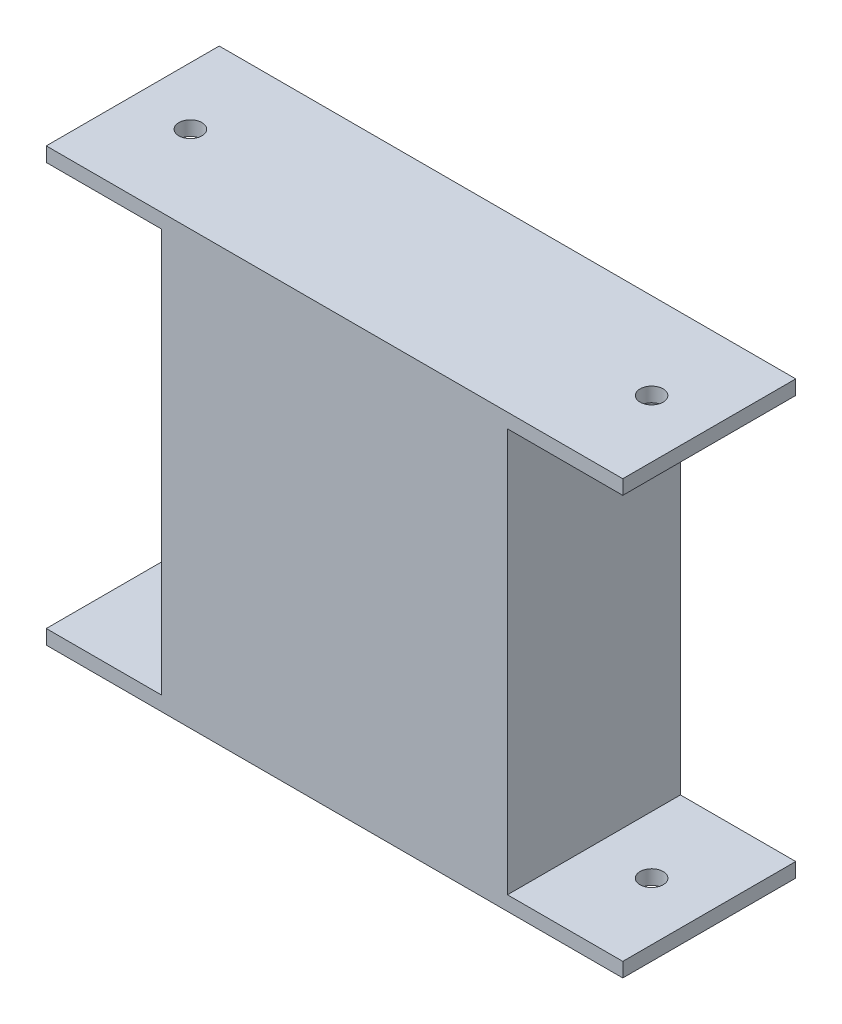
SolidWorks part; units mm, degrees
ref_plane "前视基准面" through (0, 0, 0) normal (0, 0, 1) x (1, 0, 0)
ref_plane "上视基准面" through (0, 0, 0) normal (0, 1, 0) x (1, 0, 0)
ref_plane "右视基准面" through (0, 0, 0) normal (1, 0, 0) x (0, 0, -1)
other "Configuration Table"
sketch "草图1" plane through (0, 0, 0) normal (0, 0, 1) x (1, 0, 0)
  line L0 (-100, 75) -> (100, 75)
  line L1 (-100, -75) -> (100, -75) construction
  line L2 (-100, -75) -> (-100, 75) construction
  line L3 (-100, 75) -> (100, 75) construction
  line L4 (100, -75) -> (100, 75) construction
  line L5 (-100, -75) -> (100, 75) construction
  line L6 (-100, 75) -> (100, -75) construction
  line L7 (-60, -75) -> (60, -75) construction
  line L8 (-60, -75) -> (-60, 75) construction
  line L9 (-60, 75) -> (60, 75) construction
  line L10 (60, -75) -> (60, 75) construction
  line L11 (-60, -75) -> (60, 75) construction
  line L12 (-60, 75) -> (60, -75) construction
  line L13 (-100, -70) -> (100, -70) construction
  line L14 (-100, -70) -> (-100, 70) construction
  line L15 (-100, 70) -> (100, 70) construction
  line L16 (100, -70) -> (100, 70) construction
  line L17 (-100, -70) -> (100, 70) construction
  line L18 (-100, 70) -> (100, -70) construction
  line L19 (100, 75) -> (100, 70)
  line L20 (100, 70) -> (60, 70)
  line L21 (60, 70) -> (60, -70)
  line L22 (60, -70) -> (100, -70)
  line L23 (100, -70) -> (100, -75)
  line L24 (100, -75) -> (-100, -75)
  line L25 (-100, -75) -> (-100, -70)
  line L26 (-100, -70) -> (-60, -70)
  line L27 (-60, -70) -> (-60, 70)
  line L28 (-60, 70) -> (-100, 70)
  line L29 (-100, 70) -> (-100, 75)
  point P0 (0, 0)
  point P6 (0, 0)
  point P11 (0, 0)
  dimension "D1" = 150
  dimension "D2" = 200
  dimension "D3" = 120
  dimension "D4" = 140
extrude "凸台-拉伸1" add sketch "草图1" along normal blind 60
sketch3d "3D草图2"
  point P0 (-14.2591, 19.067, 60)
ref_plane "基准面2" through (0, 0, 60) normal (0, 0, 1) x (1, 0, 0)
sketch3d "3D草图3"
  point P0 (14.1533, -75, 27.0095)
ref_plane "基准面3" through (0, -75, 0) normal (0, -1, 0) x (1, 0, 0)
sketch "草图4" plane through (0, -75, 0) normal (0, -1, 0) x (1, 0, 0)
  line L0 (0, 60) -> (0, 0) construction
  line L1 (-100, 60) -> (100, 60) construction
  line L2 (-100, 60) -> (-100, 0) construction
  line L3 (-100, 0) -> (100, 0) construction
  line L4 (100, 60) -> (100, 0) construction
  line L5 (100, 30) -> (-100, 30) construction
  line L7 (-100, 30) -> (-80, 30) construction
  circle A0 centre (-80, 30) radius 4
  circle A1 centre (80, 30) radius 4
  point P12 (0, 30)
extrude "切除-拉伸3" cut sketch "草图4" against normal blind 198
